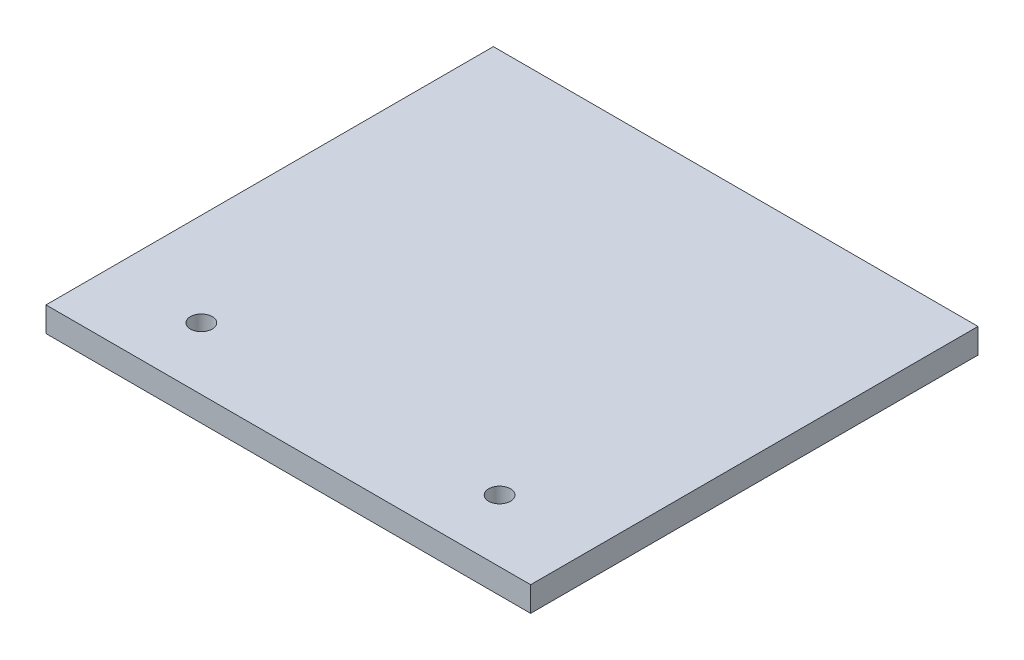
SolidWorks part; units mm, degrees
ref_plane "Front Plane" through (0, 0, 0) normal (0, 0, 1) x (1, 0, 0)
ref_plane "Top Plane" through (0, 0, 0) normal (0, 1, 0) x (1, 0, 0)
ref_plane "Right Plane" through (0, 0, 0) normal (1, 0, 0) x (0, 0, -1)
sketch "Sketch1" plane through (0, 0, 0) normal (0, 1, 0) x (1, 0, 0)
  line L1 (-39, -36) -> (39, -36)
  line L2 (-39, -36) -> (-39, 36)
  line L3 (-39, 36) -> (39, 36)
  line L4 (39, -36) -> (39, 36)
  circle A0 centre (-24, -26) radius 1.75
  circle A1 centre (24, -26) radius 1.75
extrude "Tray_Base_Extrude" add sketch "Sketch1" along normal blind 4
equation "\"ValveDiameter\" = 50mm"
equation "\"MotorGearTeeth\" = 40"
equation "\"OutputGearTeeth\" = 80"
equation "\"GearModule\" = 1.5mm"
equation "\"PressureAngle\" = 20deg"
equation "\"GearCenterDistance\" = 90mm"
equation "\"GearWidth\" = 18mm"
equation "\"OutputShaftDiameter\" = 20mm"
equation "\"BearingOD\" = 47mm"
equation "\"BearingWidth\" = 14mm"
equation "\"PlateThickness\" = 6mm"
equation "\"ValveRotation\" = 90deg"
